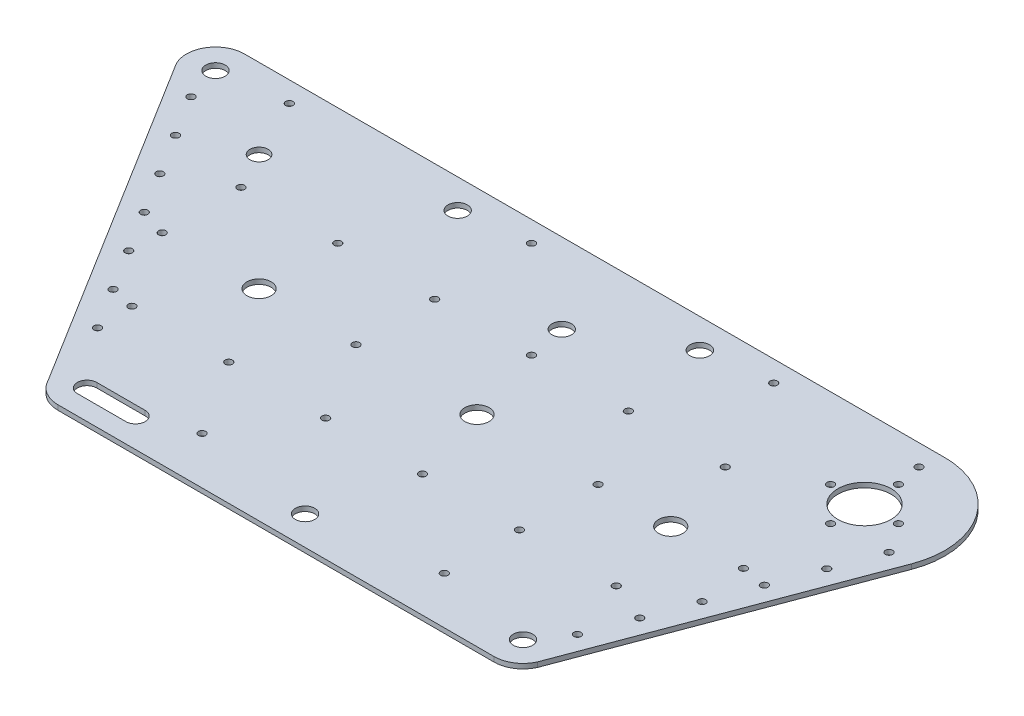
SolidWorks part; units mm, degrees
ref_plane "Front Plane" through (0, 0, 0) normal (0, 0, 1) x (1, 0, 0)
ref_plane "Top Plane" through (0, 0, 0) normal (0, 1, 0) x (1, 0, 0)
ref_plane "Right Plane" through (0, 0, 0) normal (1, 0, 0) x (0, 0, -1)
sketch "Sketch1" plane through (0, 0, 0) normal (0, 1, 0) x (1, 0, 0)
  line L0 (-106.0052, 144.9436) -> (182.9631, 145.1977)
  line L1 (160.992, -19) -> (-18.999, -19)
  line L2 (171.9001, -12) -> (214.069, 100.3323)
  line L3 (-18.999, -3) -> (1, -3)
  line L4 (0.9999, -11) -> (-18.9991, -11)
  line L5 (-29.7001, -12.4286) -> (-116.0855, 126.6112)
  line L6 (-18.9991, -18) -> (-18.8768, -17.9993)
  ellipse E0 centre (-105.9947, 133) end of major axis (-105.9947, 137) minor radius 3.9998
  ellipse E1 centre (160.992, -7) end of major axis (160.992, -3) minor radius 3.9998
  ellipse E2 centre (-18.9991, -7) end of major axis (-18.9991, -11) minor radius 3.9998 (-18.999, -3) -> (-18.9991, -11) ccw
  ellipse E3 centre (182.9908, 112) end of major axis (182.9908, 123) minor radius 10.9995
  ellipse E4 centre (-105.9947, 133) end of major axis (-105.9947, 144.9436) minor radius 11.943 (-106.0052, 144.9436) -> (-116.0855, 126.6112) ccw
  ellipse E5 centre (182.9908, 112) end of major axis (182.9909, 145.1977) minor radius 33.196 (214.069, 100.3323) -> (182.9617, 145.1977) ccw
  ellipse E6 centre (1, -7) end of major axis (1, -3) minor radius 3.9998 (0.9999, -11) -> (1, -3) ccw
  ellipse E7 centre (182.9908, 126) end of major axis (182.9908, 127.5) minor radius 1.4999
  ellipse E8 centre (196.9901, 112) end of major axis (196.9901, 113.5) minor radius 1.4999
  ellipse E9 centre (168.9915, 112) end of major axis (168.9915, 113.5) minor radius 1.4999
  ellipse E10 centre (182.9908, 98) end of major axis (182.9908, 99.5) minor radius 1.4999
  ellipse E11 centre (-18.9991, -7) end of major axis (-18.999, 5) minor radius 11.9994 (-29.7019, -12.4256) -> (-18.999, -19) ccw
  ellipse E12 centre (160.992, -7) end of major axis (160.992, 5) minor radius 11.9994 (160.992, -19) -> (171.9001, -12) ccw
  ellipse E13 centre (120.9939, 0.5) end of major axis (120.994, 2) minor radius 1.4999
  ellipse E14 centre (20.9989, 0.5) end of major axis (20.9989, 2) minor radius 1.4999
  ellipse E15 centre (120.9939, 64) end of major axis (120.994, 65.5) minor radius 1.4999
  ellipse E16 centre (20.9989, 64) end of major axis (20.9989, 65.5) minor radius 1.4999
  ellipse E17 centre (-58.997, 64) end of major axis (-58.997, 65.5) minor radius 1.4999
  ellipse E18 centre (180.9909, 64) end of major axis (180.9909, 65.5) minor radius 1.4999
  ellipse E19 centre (-78.996, 136.5) end of major axis (-78.996, 138) minor radius 1.4999
  ellipse E20 centre (20.9989, 136.5) end of major axis (20.9989, 138) minor radius 1.4999
  ellipse E21 centre (120.9939, 136.5) end of major axis (120.994, 138) minor radius 1.4999
  ellipse E22 centre (60.9969, 96.5) end of major axis (60.9969, 98) minor radius 1.4999
  ellipse E23 centre (140.9929, 96.5) end of major axis (140.9929, 98) minor radius 1.4999
  ellipse E24 centre (160.992, 31.5) end of major axis (160.992, 33) minor radius 1.4999
  ellipse E25 centre (80.996, 31.5) end of major axis (80.996, 33) minor radius 1.4999
  ellipse E26 centre (-18.9991, 96.5) end of major axis (-18.9991, 98) minor radius 1.4999
  ellipse E27 centre (-38.998, 31.5) end of major axis (-38.998, 33) minor radius 1.4999
  ellipse E28 centre (-18.9991, 64) end of major axis (-18.999, 69) minor radius 4.9997
  ellipse E29 centre (70.9964, 64) end of major axis (70.9965, 69) minor radius 4.9997
  ellipse E30 centre (150.9924, 64) end of major axis (150.9924, 69) minor radius 4.9997
  ellipse E31 centre (-101.6892, 118.5984) end of major axis (-101.6892, 120.0984) minor radius 1.4999
  ellipse E32 centre (-91.1347, 101.6106) end of major axis (-91.1347, 103.1106) minor radius 1.4999
  ellipse E33 centre (-80.5803, 84.623) end of major axis (-80.5803, 86.123) minor radius 1.4999
  ellipse E34 centre (-70.0255, 67.6347) end of major axis (-70.0255, 69.1347) minor radius 1.4999
  ellipse E35 centre (-59.4708, 50.6466) end of major axis (-59.4708, 52.1466) minor radius 1.4999
  ellipse E36 centre (-48.9163, 33.6588) end of major axis (-48.9163, 35.1588) minor radius 1.4999
  ellipse E37 centre (-38.3619, 16.6713) end of major axis (-38.3619, 18.1713) minor radius 1.4999
  ellipse E38 centre (205.3225, 99.7958) end of major axis (205.3225, 101.2958) minor radius 1.4999
  ellipse E39 centre (198.3244, 81.0602) end of major axis (198.3244, 82.5602) minor radius 1.4999
  ellipse E40 centre (191.3265, 62.3248) end of major axis (191.3265, 63.8248) minor radius 1.4999
  ellipse E41 centre (184.3286, 43.5896) end of major axis (184.3286, 45.0896) minor radius 1.4999
  ellipse E42 centre (177.3307, 24.8545) end of major axis (177.3307, 26.3545) minor radius 1.4999
  ellipse E43 centre (170.3325, 6.1186) end of major axis (170.3325, 7.6186) minor radius 1.4999
  ellipse E44 centre (180.9909, 136.5) end of major axis (180.9909, 138) minor radius 1.4999
  ellipse E45 centre (20.9989, 96.5) end of major axis (20.9989, 98) minor radius 1.4999
  ellipse E46 centre (100.995, 96.5) end of major axis (100.995, 98) minor radius 1.4999
  ellipse E47 centre (-58.9971, 96.5) end of major axis (-58.997, 98) minor radius 1.4999
  ellipse E48 centre (0.9999, 31.5) end of major axis (1, 33) minor radius 1.4999
  ellipse E49 centre (40.9979, 31.5) end of major axis (40.9979, 33) minor radius 1.4999
  ellipse E50 centre (120.9939, 31.5) end of major axis (120.994, 33) minor radius 1.4999
  ellipse E51 centre (-66.9967, 112) end of major axis (-66.9966, 115.75) minor radius 3.7498
  ellipse E52 centre (57.9971, 112) end of major axis (57.9971, 116) minor radius 3.9998
  ellipse E53 centre (-5.9997, 133) end of major axis (-5.9997, 137) minor radius 3.9998
  ellipse E54 centre (93.9952, 133) end of major axis (93.9952, 137) minor radius 3.9998
  ellipse E55 centre (70.9964, -7) end of major axis (70.9965, -3) minor radius 3.9998
extrude "Boss-Extrude1" add sketch "Sketch1" along normal blind 2
